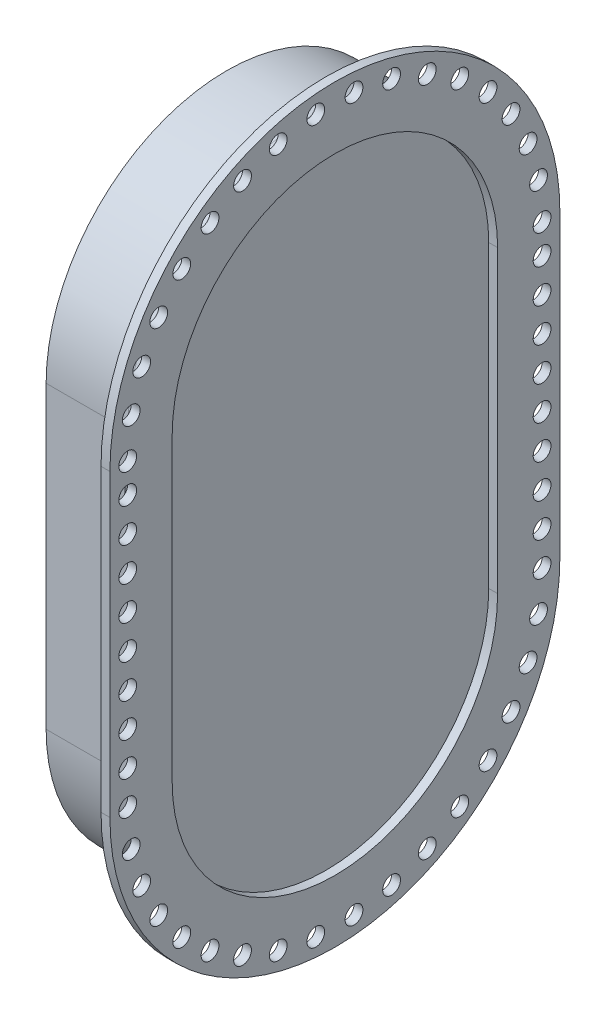
SolidWorks part; units mm, degrees
ref_plane "Front Plane" through (0, 0, 0) normal (0, 0, 1) x (1, 0, 0)
ref_plane "Top Plane" through (0, 0, 0) normal (0, 1, 0) x (1, 0, 0)
ref_plane "Right Plane" through (0, 0, 0) normal (1, 0, 0) x (0, 0, -1)
sketch "Sketch1" plane through (0, 0, 0) normal (1, 0, 0) x (0, 0, -1)
  line L0 (0, -73.5249) -> (0, 94.9573) construction
  line L1 (-91.5, -73.5249) -> (-91.5, 94.9573)
  line L2 (91.5, -73.5249) -> (91.5, 94.9573)
  line L3 (-101.5, -73.5249) -> (-101.5, 94.9573)
  line L4 (101.5, -73.5249) -> (101.5, 94.9573)
  arc A0 (-91.5, -73.5249) -> (91.5, -73.5249) centre (0, -73.5249) ccw
  arc A1 (91.5, 94.9573) -> (-91.5, 94.9573) centre (0, 94.9573) ccw
  arc A2 (101.5, 94.9573) -> (-101.5, 94.9573) centre (0, 94.9573) ccw
  arc A3 (-101.5, -73.5249) -> (101.5, -73.5249) centre (0, -73.5249) ccw
  point P3 (0, 10.7162)
  dimension "D2" = 91.5
  dimension "D1" = 168.4822
  dimension "D3" = 10
extrude "Boss-Extrude1" add sketch "Sketch1" along normal blind 60.8698
sketch "Sketch2" plane through (60.8698, 0, 0) normal (1, 0, 0) x (0, 0, -1)
  line L0 (-126.5, 94.9573) -> (-126.5, -73.5249)
  line L1 (126.5, -73.5249) -> (126.5, 94.9573)
  line L2 (101.5, -73.5249) -> (101.5, 94.9573)
  line L3 (-101.5, 94.9573) -> (-101.5, -73.5249)
  line L4 (101.5, -73.5249) -> (101.5, 94.9573)
  line L5 (-101.5, 94.9573) -> (-101.5, -73.5249)
  arc A0 (-126.5, -73.5249) -> (126.5, -73.5249) centre (0, -73.5249) ccw
  arc A1 (126.5, 94.9573) -> (-126.5, 94.9573) centre (0, 94.9573) ccw
  arc A2 (-101.5, -73.5249) -> (101.5, -73.5249) centre (0, -73.5249) ccw
  arc A3 (101.5, 94.9573) -> (-101.5, 94.9573) centre (0, 94.9573) ccw
  arc A4 (-101.5, -73.5249) -> (101.5, -73.5249) centre (0, -73.5249) ccw
  arc A5 (101.5, 94.9573) -> (-101.5, 94.9573) centre (0, 94.9573) ccw
  dimension "D1" = 0
  dimension "D2" = 25
extrude "Boss-Extrude2" add sketch "Sketch2" against normal blind 5
fillet "Fillet1" radius 10 4 edges at (55.8698, 10.7162, -101.5) (55.8698, -175.0249, 0) (55.8698, 10.7162, 101.5) (55.8698, 196.4573, 0)
sketch "Sketch3" plane through (55.8698, 0, 0) normal (-1, 0, 0) x (0, 0, 1)
  line L8 (116.5, -73.5249) -> (116.5, 94.9573)
  line L9 (-116.5, 94.9573) -> (-116.5, -73.5249)
  line L10 (116.5, -73.5249) -> (116.5, 94.9573)
  line L11 (-116.5, 94.9573) -> (-116.5, -73.5249)
  circle A0 centre (-116.5, -73.5249) radius 5
  circle A1 centre (116.5, -73.5249) radius 5
  circle A2 centre (116.5, 94.9573) radius 5
  circle A3 centre (-116.5, 94.9573) radius 5
  arc A6 (-116.5, -73.5249) -> (116.5, -73.5249) centre (0, -73.5249) ccw
  arc A7 (116.5, 94.9573) -> (-116.5, 94.9573) centre (0, 94.9573) ccw
  arc A8 (-116.5, -73.5249) -> (116.5, -73.5249) centre (0, -73.5249) ccw construction
  arc A9 (116.5, 94.9573) -> (-116.5, 94.9573) centre (0, 94.9573) ccw
  circle A11 centre (-116.5, -54.5249) radius 5
  circle A12 centre (-116.5, -35.5249) radius 5
  circle A13 centre (-116.5, -16.5249) radius 5
  circle A14 centre (-116.5, 2.4751) radius 5
  circle A15 centre (-116.5, 21.4751) radius 5
  circle A16 centre (-116.5, 40.4751) radius 5
  circle A17 centre (-116.5, 59.4751) radius 5
  circle A18 centre (-116.5, 78.4751) radius 5
  circle A19 centre (116.5, -54.5249) radius 5
  circle A20 centre (116.5, -35.5249) radius 5
  circle A21 centre (116.5, -16.5249) radius 5
  circle A22 centre (116.5, 2.4751) radius 5
  circle A23 centre (116.5, 21.4751) radius 5
  circle A24 centre (116.5, 40.4751) radius 5
  circle A25 centre (116.5, 59.4751) radius 5
  circle A26 centre (116.5, 78.4751) radius 5
  circle A27 centre (-114.5164, 116.3641) radius 5
  circle A28 centre (-108.633, 137.042) radius 5
  circle A29 centre (-99.0503, 156.2867) radius 5
  circle A30 centre (-86.0945, 173.4429) radius 5
  circle A31 centre (-70.2069, 187.9263) radius 5
  circle A32 centre (-51.9285, 199.2438) radius 5
  circle A33 centre (-31.8817, 207.01) radius 5
  circle A34 centre (-10.7493, 210.9603) radius 5
  circle A35 centre (10.7493, 210.9603) radius 5
  circle A36 centre (31.8817, 207.01) radius 5
  circle A37 centre (51.9285, 199.2438) radius 5
  circle A38 centre (70.2069, 187.9263) radius 5
  circle A39 centre (86.0945, 173.4429) radius 5
  circle A40 centre (99.0503, 156.2867) radius 5
  circle A41 centre (108.633, 137.042) radius 5
  circle A42 centre (114.5164, 116.3641) radius 5
  circle A43 centre (116.5, 94.9573) radius 5
  circle A44 centre (-114.5164, -94.9318) radius 5
  circle A45 centre (-108.633, -115.6096) radius 5
  circle A46 centre (-99.0503, -134.8543) radius 5
  circle A47 centre (-86.0945, -152.0105) radius 5
  circle A48 centre (-70.2069, -166.4939) radius 5
  circle A49 centre (-51.9285, -177.8115) radius 5
  circle A50 centre (-31.8817, -185.5776) radius 5
  circle A51 centre (-10.7493, -189.528) radius 5
  circle A52 centre (10.7493, -189.528) radius 5
  circle A53 centre (31.8817, -185.5776) radius 5
  circle A54 centre (51.9285, -177.8115) radius 5
  circle A55 centre (70.2069, -166.4939) radius 5
  circle A56 centre (86.0945, -152.0105) radius 5
  circle A57 centre (99.0503, -134.8543) radius 5
  circle A58 centre (108.633, -115.6096) radius 5
  circle A59 centre (114.5164, -94.9318) radius 5
  circle A60 centre (116.5, -73.5249) radius 5
  point P81 (0, 94.9573)
  point P116 (0, -73.5249)
  dimension "D1" = 5
  dimension "D2" = 9
  dimension "D3" = 9
  dimension "D4" = 18
  dimension "D5" = 18
extrude "Cut-Extrude1" cut sketch "Sketch3" against normal blind 5
